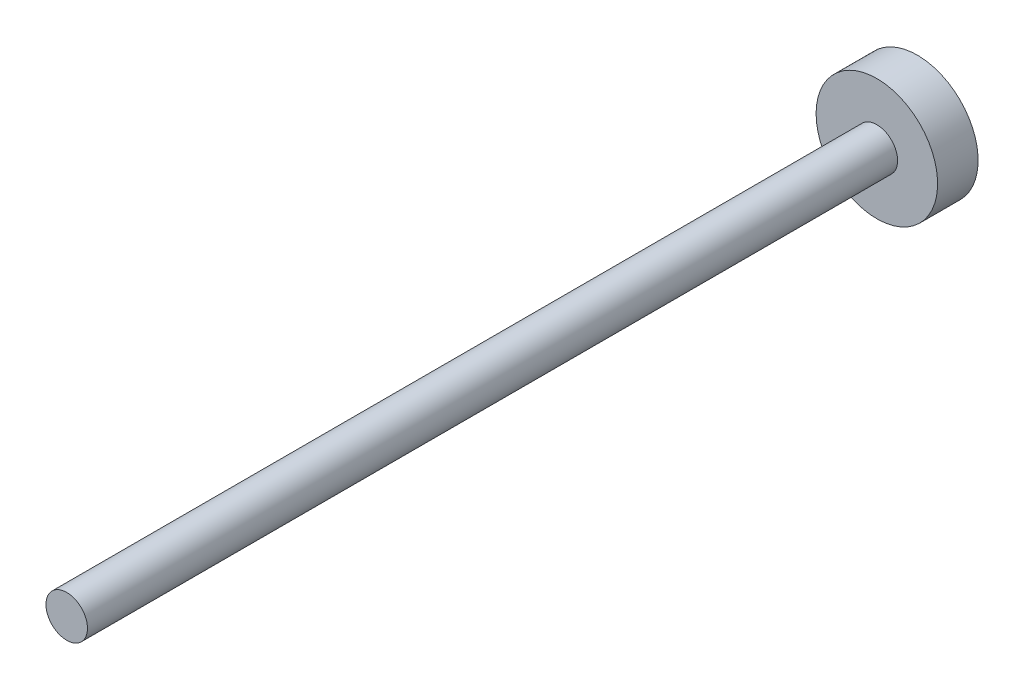
SolidWorks part; units mm, degrees
ref_plane "Front Plane" through (0, 0, 0) normal (0, 0, 1) x (1, 0, 0)
ref_plane "Top Plane" through (0, 0, 0) normal (0, 1, 0) x (1, 0, 0)
ref_plane "Right Plane" through (0, 0, 0) normal (1, 0, 0) x (0, 0, -1)
sketch "Sketch1" plane through (0, 0, 0) normal (0, 0, 1) x (1, 0, 0)
  circle A0 centre (0, 0) radius 2.05
  dimension "D1" = 4.1
extrude "Boss-Extrude1" add sketch "Sketch1" along normal blind 80
sketch "Sketch2" plane through (0, 0, 0) normal (0, 0, -1) x (-1, 0, 0)
  circle A0 centre (0, 0) radius 6
  dimension "D1" = 12
extrude "Boss-Extrude2" add sketch "Sketch2" along normal blind 4
